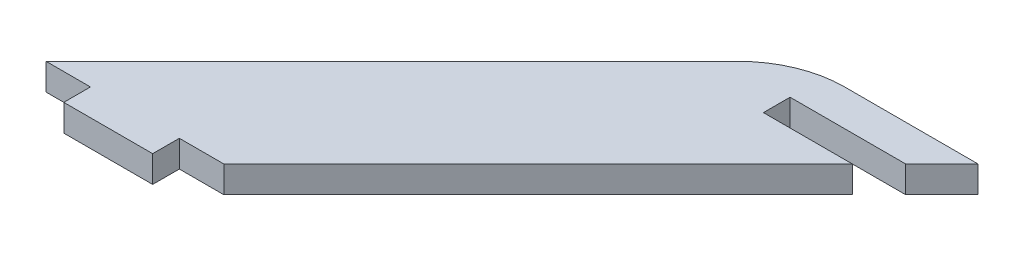
SolidWorks part; units mm, degrees
ref_plane "Plano frontal" through (0, 0, 0) normal (0, 0, 1) x (1, 0, 0)
ref_plane "Plano superior" through (0, 0, 0) normal (0, 1, 0) x (1, 0, 0)
ref_plane "Plano direito" through (0, 0, 0) normal (1, 0, 0) x (0, 0, -1)
sketch "Esboço1" plane through (0, 0, 0) normal (0, 1, 0) x (1, 0, 0)
  line L0 (-12.9893, -17.5403) -> (-2.9893, -17.5403)
  line L1 (-2.9893, -17.5403) -> (-2.9893, -14.5403)
  line L2 (-2.9893, -14.5403) -> (2.0107, -14.5403)
  line L3 (-12.9893, -17.5403) -> (-12.9893, -14.5403)
  line L4 (-12.9893, -14.5403) -> (-17.9893, -14.5403)
  line L5 (-17.9893, -14.5403) -> (20.9016, 24.3506)
  line L6 (2.0107, -14.5403) -> (37.3661, 20.815)
  line L7 (37.3661, 20.815) -> (27.3661, 20.815)
  line L8 (27.3661, 20.815) -> (27.3661, 23.815)
  line L9 (40.3661, 23.815) -> (27.3661, 23.815)
  line L11 (29.4372, 27.8861) -> (44.4372, 27.8861)
  line L12 (44.4372, 27.8861) -> (40.3661, 23.815)
  arc A0 (20.9016, 24.3506) -> (29.4372, 27.8861) centre (29.4372, 15.815) cw
extrude "Ressalto-extrusão1" add sketch "Esboço1" along normal blind 3
